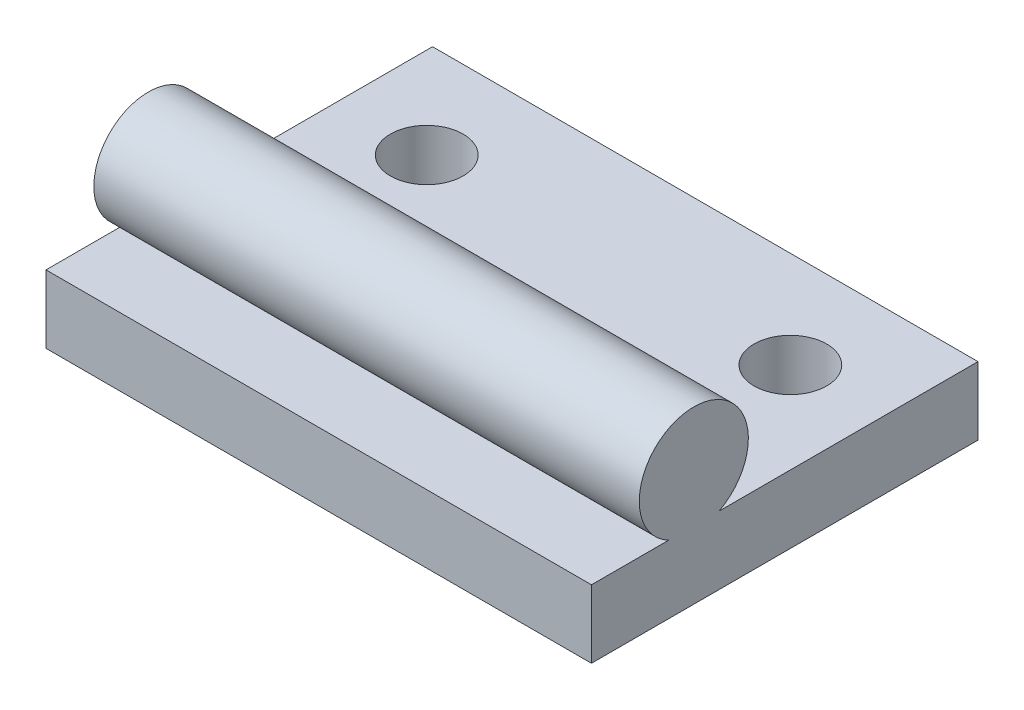
SolidWorks part; units mm, degrees
ref_plane "Front Plane" through (0, 0, 0) normal (0, 0, 1) x (1, 0, 0)
ref_plane "Top Plane" through (0, 0, 0) normal (0, 1, 0) x (1, 0, 0)
ref_plane "Right Plane" through (0, 0, 0) normal (1, 0, 0) x (0, 0, -1)
sketch "Sketch1" plane through (0, 0, 0) normal (0, 1, 0) x (1, 0, 0)
  line L0 (0, 0) -> (38.1, 0)
  line L1 (0, 0) -> (0, 12.7)
  line L2 (38.1, 0) -> (38.1, 12.7)
  line L3 (0, 12.7) -> (38.1, 12.7)
extrude "Boss-Extrude1" add sketch "Sketch1" along normal blind 4.7498
sketch "Sketch2" plane through (0, 4.7498, 0) normal (0, 1, 0) x (1, 0, 0)
  line L0 (19.05, 0) -> (19.05, 5.9436) construction
  line L1 (0, 0) -> (38.1, 0) construction
  line L2 (31.75, 5.9436) -> (6.35, 5.9436) construction
  circle A0 centre (6.35, 5.9436) radius 2.54
  circle A1 centre (31.75, 5.9436) radius 2.54
  point P7 (19.05, 5.9436)
extrude "Cut-Extrude1" cut sketch "Sketch2" against normal blind 4.7498
sketch "Sketch4" plane through (0, 0, 0) normal (0, 0, 1) x (1, 0, 0)
  line L0 (0, 4.7498) -> (38.1, 4.7498)
  line L1 (0, 4.7498) -> (0, -0.0001)
  line L2 (38.1, 4.7498) -> (38.1, -0.0001)
  line L3 (0, -0.0001) -> (38.1, -0.0001)
extrude "Boss-Extrude2" add sketch "Sketch4" along normal blind 14.3002
sketch "Sketch5" plane through (0, 0, 0) normal (-1, 0, 0) x (0, 0, 1)
  line L0 (7.1501, -0.0001) -> (7.1501, 8.1279) construction
  line L1 (14.3002, -0.0001) -> (0, -0.0001) construction
  circle A0 centre (7.1501, 8.1279) radius 3.81
extrude "Boss-Extrude3" add sketch "Sketch5" against normal up to surface (38.1 mm away) up to face at (38.1, 1.8999, 3.3401)
